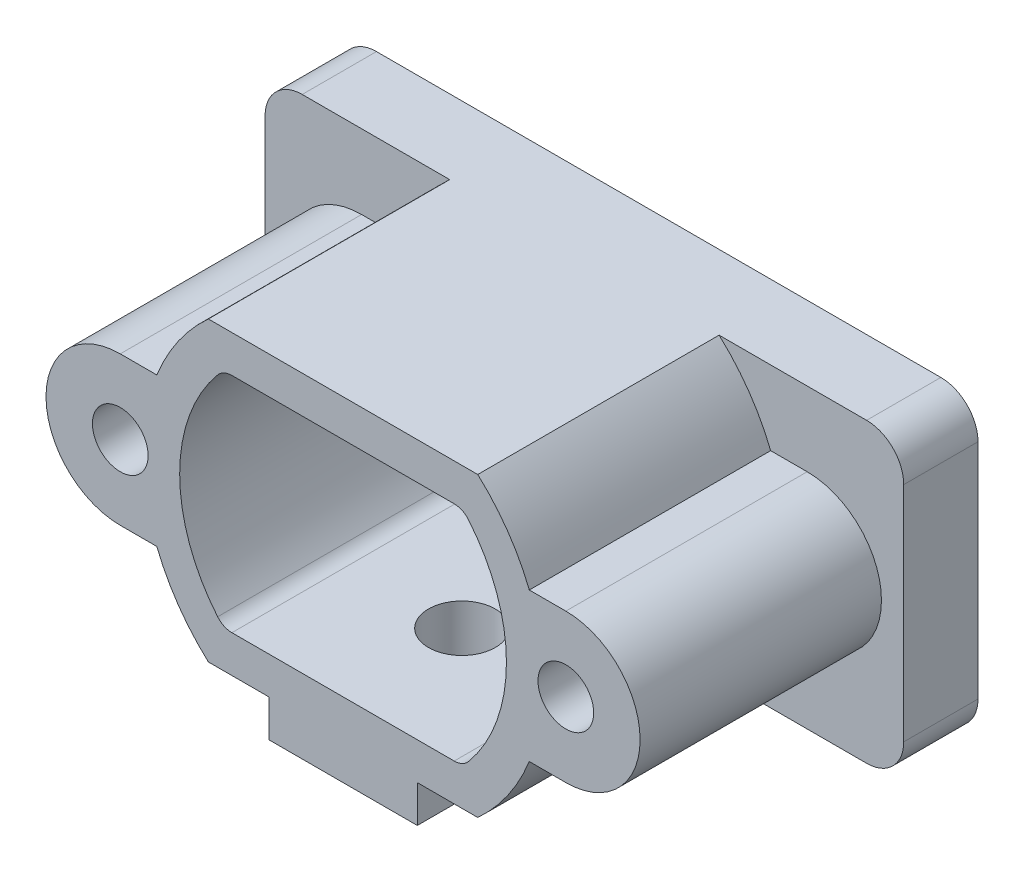
SolidWorks part; units mm, degrees
ref_plane "前视基准面" through (0, 0, 0) normal (0, 0, 1) x (1, 0, 0)
ref_plane "上视基准面" through (0, 0, 0) normal (0, 1, 0) x (1, 0, 0)
ref_plane "右视基准面" through (0, 0, 0) normal (1, 0, 0) x (0, 0, -1)
sketch "草图1" plane through (0, 0, 0) normal (0, 0, 1) x (1, 0, 0)
  line L1 (76, -40) -> (-76, -40)
  line L2 (86, -30) -> (86, 30)
  line L3 (76, 40) -> (-76, 40)
  line L4 (-86, -30) -> (-86, 30)
  line L5 (86, -40) -> (-86, 40) construction
  line L6 (86, 40) -> (-86, -40) construction
  arc A0 (76, -40) -> (86, -30) centre (76, -30) ccw
  arc A1 (86, 30) -> (76, 40) centre (76, 30) ccw
  arc A2 (-86, -30) -> (-76, -40) centre (-76, -30) ccw
  arc A3 (-86, 30) -> (-76, 40) centre (-76, 30) cw
  point P1 (0, 0)
  dimension "D3" = 10
  dimension "D1" = 80
  dimension "D2" = 172
extrude "凸台-拉伸1" add sketch "草图1" along normal blind 20
sketch "草图3" plane through (0, 0, 20) normal (0, 0, 1) x (1, 0, 0)
  line L0 (-36.2767, 40) -> (36.2767, 40)
  line L1 (32.187, -30) -> (-32.187, -30)
  line L2 (76, 40) -> (-76, 40) construction
  line L3 (32.187, 30) -> (-32.187, 30)
  line L4 (-36.2767, -40) -> (36.2767, -40)
  line L5 (40.2675, -30) -> (-37.9971, 28.3085) construction
  line L6 (40.2675, 30) -> (-40.2675, -30) construction
  line L7 (-76, -40) -> (76, -40) construction
  line L8 (-50.1597, 20) -> (-60, 20)
  line L9 (60, -20) -> (50.1597, -20)
  line L10 (-50.1597, -20) -> (-60, -20)
  line L11 (60, 20) -> (50.1597, 20)
  line L12 (48, -16) -> (-60, 20) construction
  line L13 (60, -20) -> (51.2289, -17.0763) construction
  line L14 (60, 20) -> (-60, -20) construction
  arc A0 (-36.2767, 40) -> (-50.1597, 20) centre (0, 0) ccw
  arc A1 (32.187, -30) -> (32.187, 30) centre (0, 0) ccw
  arc A2 (-32.187, 30) -> (-32.187, -30) centre (0, 0) ccw
  arc A3 (36.2767, -40) -> (50.1597, -20) centre (0, 0) ccw
  arc A4 (-60, 20) -> (-60, -20) centre (-60, 0) ccw
  arc A5 (50.1597, 20) -> (36.2767, 40) centre (0, 0) ccw
  arc A6 (60, -20) -> (60, 20) centre (60, 0) ccw
  arc A7 (-50.1597, -20) -> (-36.2767, -40) centre (0, 0) ccw
  dimension "D1" = 108
  dimension "D3" = 88
  dimension "D4" = 40
  dimension "D2" = 60
  dimension "D6" = 60
  dimension "D7" = 60
extrude "凸台-拉伸2" add sketch "草图3" along normal blind 65
sketch "草图4" plane through (0, 0, 85) normal (0, 0, 1) x (1, 0, 0)
  circle A0 centre (-60, 0) radius 7.5
  circle A1 centre (60, 0) radius 7.5
  dimension "D1" = 15
  dimension "D2" = 15
extrude "切除-拉伸1" cut sketch "草图4" against normal blind 85
sketch "草图5" plane through (0, 0, 20) normal (0, 0, 1) x (1, 0, 0)
  line L0 (-18.7083, -12.5) -> (-30, -12.5)
  line L1 (30, -12.5) -> (18.7083, -12.5)
  line L2 (30, -12.5) -> (30, 12.5)
  line L3 (30, 12.5) -> (18.7083, 12.5)
  line L4 (-30, -12.5) -> (-30, 12.5)
  line L5 (30, -12.5) -> (-30, 12.5) construction
  line L6 (30, 12.5) -> (-30, -12.5) construction
  line L7 (-18.7083, 12.5) -> (-30, 12.5)
  arc A0 (-18.7083, -12.5) -> (18.7083, -12.5) centre (0, 0) ccw
  arc A1 (18.7083, 12.5) -> (-18.7083, 12.5) centre (0, 0) ccw
  point P0 (0, 0)
  dimension "D3" = 45
  dimension "D1" = 60
  dimension "D2" = 25
extrude "切除-拉伸2" cut sketch "草图5" against normal blind 20
sketch "草图6" plane through (0, -40, 0) normal (0, -1, 0) x (1, 0, 0)
  line L0 (-36.2767, 85) -> (36.2767, 85) construction
  line L2 (20, 53) -> (20, 85)
  line L3 (20, 85) -> (-20, 85)
  line L4 (-20, 53) -> (-20, 85)
  line L5 (20, 53) -> (-20, 85) construction
  line L6 (20, 85) -> (-20, 53) construction
  arc A0 (-20, 53) -> (20, 53) centre (0, 53) ccw
  point P0 (0, 69)
  dimension "D1" = 40
  dimension "D2" = 32
  dimension "D3" = 0
extrude "凸台-拉伸3" add sketch "草图6" along normal blind 10
sketch "草图7" plane through (0, -50, 0) normal (0, -1, 0) x (1, 0, 0)
  circle A0 centre (0, 53) radius 9
  dimension "D1" = 18
extrude "切除-拉伸3" cut sketch "草图7" against normal blind 20
fillet "圆角1" radius 5 4 edges at (32.187, -30, 52.5) (-32.187, -30, 52.5) (32.187, 30, 52.5) (-32.187, 30, 52.5)
